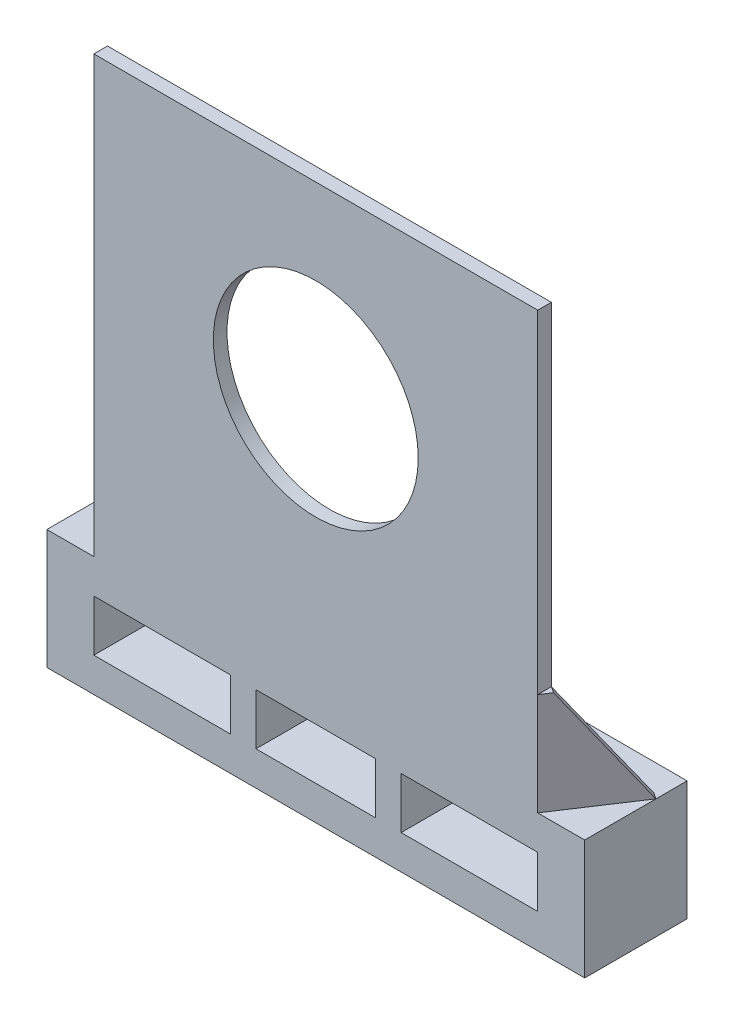
SolidWorks part; units mm, degrees
ref_plane "Front Plane" through (0, 0, 0) normal (0, 0, 1) x (1, 0, 0)
ref_plane "Top Plane" through (0, 0, 0) normal (0, 1, 0) x (1, 0, 0)
ref_plane "Right Plane" through (0, 0, 0) normal (1, 0, 0) x (0, 0, -1)
sketch "Sketch1" plane through (0, 0, 0) normal (0, 0, 1) x (1, 0, 0)
  line L1 (195, 191.25) -> (-195, 191.25)
  line L2 (195, 191.25) -> (195, -191.25)
  line L3 (195, -191.25) -> (-195, -191.25)
  line L4 (-195, 191.25) -> (-195, -191.25)
  line L5 (195, 191.25) -> (-195, -191.25) construction
  line L6 (195, -191.25) -> (-195, 191.25) construction
  circle A0 centre (0, 26.25) radius 90
  point P0 (0, 0)
  dimension "D3" = 180
  dimension "D1" = 390
  dimension "D2" = 382.5
  dimension "D4" = 165
extrude "Boss-Extrude1" add sketch "Sketch1" along normal blind 12
sketch "Sketch2" plane through (0, 0, 12) normal (0, 0, 1) x (1, 0, 0)
  line L0 (-195, -191.25) -> (195, -191.25) construction
  line L1 (236.25, -191.25) -> (-236.25, -191.25)
  line L2 (236.25, -191.25) -> (236.25, -296.25)
  line L3 (236.25, -296.25) -> (-236.25, -296.25)
  line L4 (-236.25, -191.25) -> (-236.25, -296.25)
  line L5 (236.25, -191.25) -> (-236.25, -296.25) construction
  line L6 (236.25, -296.25) -> (-236.25, -191.25) construction
  line L7 (195, -221.25) -> (75, -221.25)
  line L8 (195, -221.25) -> (195, -266.25)
  line L9 (195, -266.25) -> (75, -266.25)
  line L10 (75, -221.25) -> (75, -266.25)
  line L11 (195, -221.25) -> (75, -266.25) construction
  line L12 (195, -266.25) -> (75, -221.25) construction
  line L13 (52.5, -221.25) -> (-52.5, -221.25)
  line L14 (52.5, -221.25) -> (52.5, -266.25)
  line L15 (52.5, -266.25) -> (-52.5, -266.25)
  line L16 (-52.5, -221.25) -> (-52.5, -266.25)
  line L17 (52.5, -221.25) -> (-52.5, -266.25) construction
  line L18 (52.5, -266.25) -> (-52.5, -221.25) construction
  line L19 (-75, -221.25) -> (-195, -221.25)
  line L20 (-75, -221.25) -> (-75, -266.25)
  line L21 (-75, -266.25) -> (-195, -266.25)
  line L22 (-195, -221.25) -> (-195, -266.25)
  line L23 (-75, -221.25) -> (-195, -266.25) construction
  line L24 (-75, -266.25) -> (-195, -221.25) construction
  point P0 (0, -243.75)
  point P5 (135, -243.75)
  point P10 (0, -243.75)
  point P15 (-135, -243.75)
  dimension "D1" = 472.5
  dimension "D2" = 105
  dimension "D3" = 120
  dimension "D4" = 105
  dimension "D5" = 120
  dimension "D6" = 45
  dimension "D7" = 45
  dimension "D8" = 22.5
  dimension "D9" = 22.5
extrude "Boss-Extrude2" add sketch "Sketch2" against normal blind 90
sketch "Sketch3" plane through (0, -191.25, 0) normal (0, 1, 0) x (1, 0, 0)
  line L0 (195, -12) -> (236.25, 50.6373)
  line L1 (236.25, 78) -> (236.25, -12) construction
  line L2 (236.25, 50.6373) -> (230.7379, 54.2673)
  line L3 (230.7379, 54.2673) -> (195, 0)
  line L4 (195, -12) -> (195, 0) construction
  line L5 (195, -12) -> (195, 0) construction
  line L6 (195, 0) -> (195, -12)
  dimension "D1" = 75
extrude "Boss-Extrude3" add sketch "Sketch3" along normal blind 90
sketch "Sketch4" plane through (141.5246, 0, 93.2014) normal (0.8352, 0, 0.55) x (0.55, 0, -0.8352)
  line L0 (172.228, -101.25) -> (107.25, -101.25)
  line L1 (107.25, -101.25) -> (172.228, -191.25)
  line L2 (172.228, -191.25) -> (172.228, -101.25)
extrude "Cut-Extrude1" cut sketch "Sketch4" against normal blind 90
mirror "Mirror1" about plane through (0, 0, 0) normal (1, 0, 0) of "Cut-Extrude1", "Boss-Extrude3"
